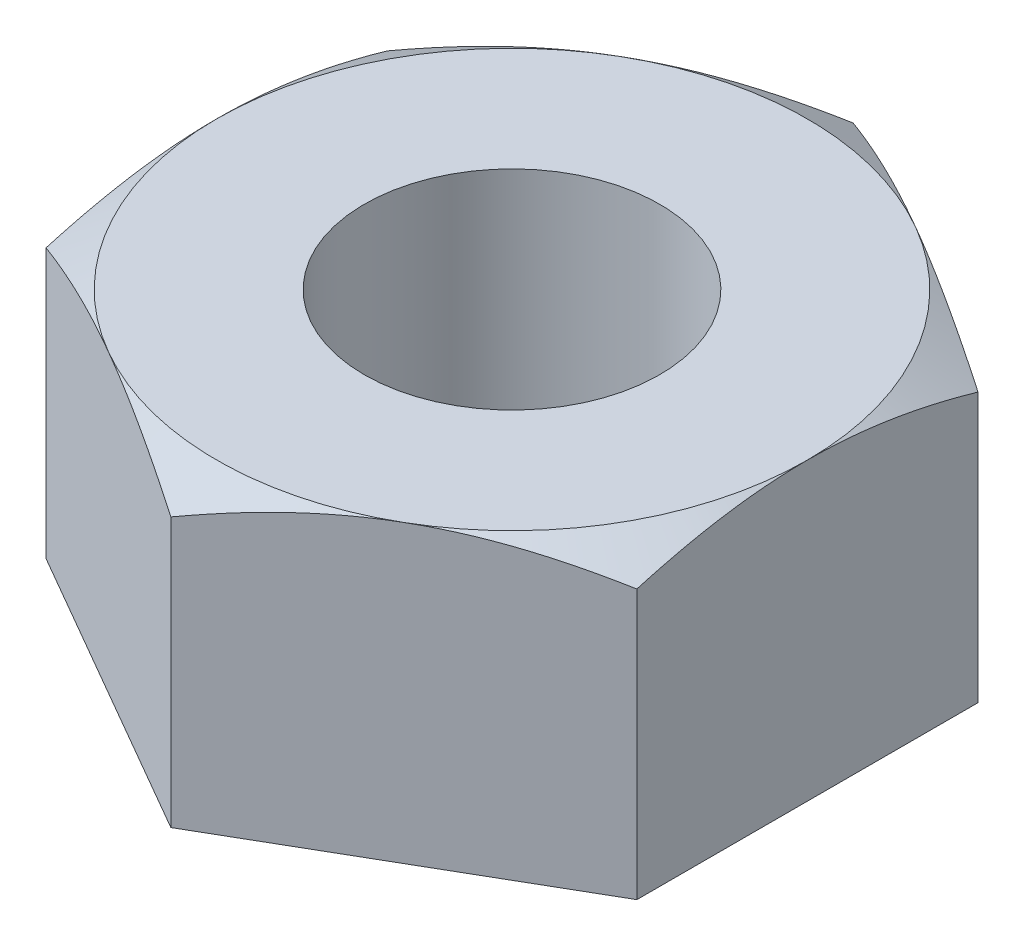
SolidWorks part; units mm, degrees
ref_plane "Front Plane" through (0, 0, 0) normal (0, 0, 1) x (1, 0, 0)
ref_plane "Top Plane" through (0, 0, 0) normal (0, 1, 0) x (1, 0, 0)
ref_plane "Right Plane" through (0, 0, 0) normal (1, 0, 0) x (0, 0, -1)
sketch "Sketch1" plane through (0, 0, 0) normal (0, 1, 0) x (1, 0, 0)
  line L1 (0, 5.7735) -> (-5, 2.8868)
  line L2 (-5, 2.8868) -> (-5, -2.8868)
  line L3 (-5, -2.8868) -> (0, -5.7735)
  line L4 (0, -5.7735) -> (5, -2.8868)
  line L5 (5, -2.8868) -> (5, 2.8868)
  line L6 (5, 2.8868) -> (0, 5.7735)
  circle A0 centre (0, 0) radius 5 construction
  dimension "NT_S" = 10
extrude "Boss-Extrude1" add sketch "Sketch1" against normal blind 5
sketch "Sketch2" plane through (0, 0, 0) normal (1, 0, 0) x (0, 0, -1)
  line L0 (0, 0) -> (0, -5) construction
  line L1 (-2.8868, -5) -> (2.8868, -5) construction
  line L2 (5, 0) -> (5.7735, 0)
  line L3 (5.7735, 0) -> (5.7735, -0.4466)
  line L4 (5.7735, -0.4466) -> (5, 0)
  line L5 (2.8868, 0) -> (5.7735, 0) construction
  line L6 (5.7735, -5) -> (5.7735, 0) construction
  dimension "D1" = 30
revolve "Cut-Revolve1" cut sketch "Sketch2" angle 360 about L0
hole_wizard "Tapped Hole1" positions "Sketch4" profile "Sketch3" tap size "M3x0.5" standard "JIS" end condition through all
sketch "Sketch4" plane through (0, 0, 0) normal (0, 1, 0) x (1, 0, 0)
  point P0 (0, 0)
sketch "Sketch3" plane through (0, 0, 0) normal (1, 0, 0) x (0, 0, 1)
  line L0 (0, 0) -> (0, 5)
  line L1 (0, 5) -> (2.5, 5)
  line L2 (2.5, 5) -> (2.5, 0)
  line L5 (2.5, 0) -> (0, 0)
  line L11 (0, 0) -> (0, 5) construction
  dimension "Thru Tap Drill Dia." = 5
  dimension "Thru Tap Drill Depth" = 5
cosmetic thread "Hole Thread1" parameters "NT_M"=6
